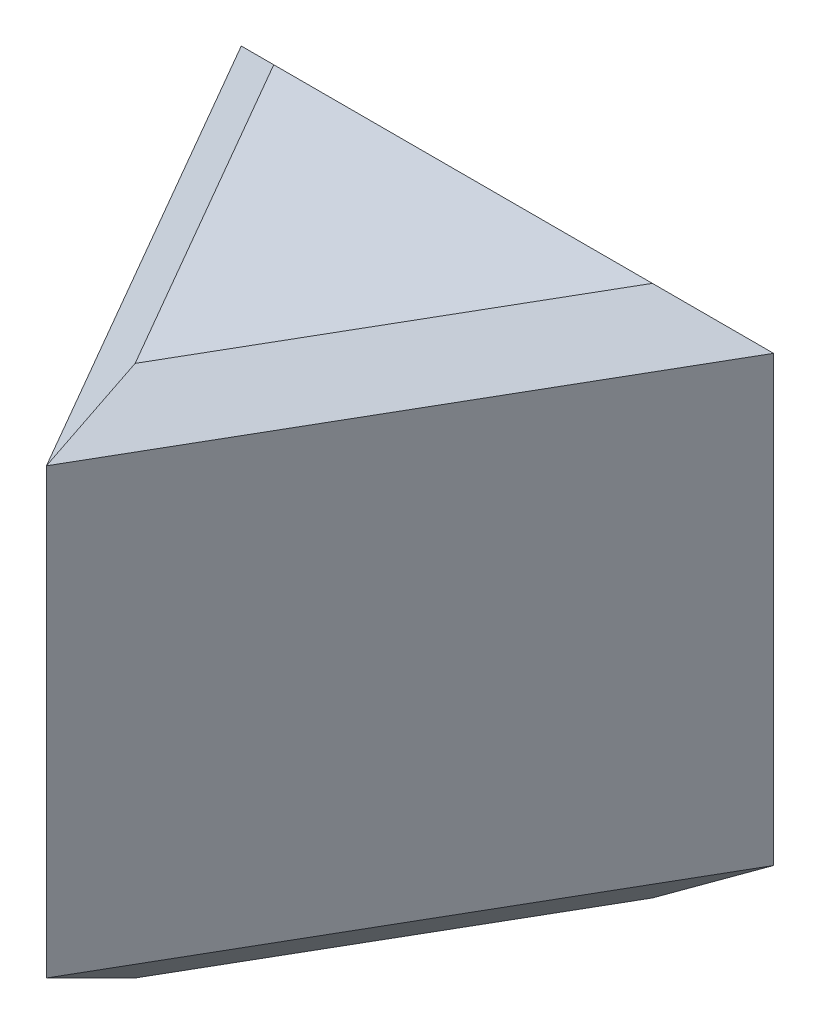
SolidWorks part; units mm, degrees
ref_plane "Front Plane" through (0, 0, 0) normal (0, 0, 1) x (1, 0, 0)
ref_plane "Top Plane" through (0, 0, 0) normal (0, 1, 0) x (1, 0, 0)
ref_plane "Right Plane" through (0, 0, 0) normal (1, 0, 0) x (0, 0, -1)
sketch "Sketch1" plane through (0, 0, 0) normal (0, 1, 0) x (1, 0, 0)
  line L1 (0, -3.4641) -> (3, 1.7321)
  line L2 (3, 1.7321) -> (-3, 1.7321)
  line L3 (-3, 1.7321) -> (0, -3.4641)
  circle A0 centre (0, 0) radius 1.7321 construction
  dimension "D1" = 6
extrude "Boss-Extrude1" add sketch "Sketch1" along normal mid plane 6
chamfer "Chamfer2" distance 0.5 angle 45 6 edges at (1.5, -3, 0.866) (0, -3, -1.7321) (-1.5, -3, 0.866) (0, 3, -1.7321) (1.5, 3, 0.866) (-1.5, 3, 0.866)
